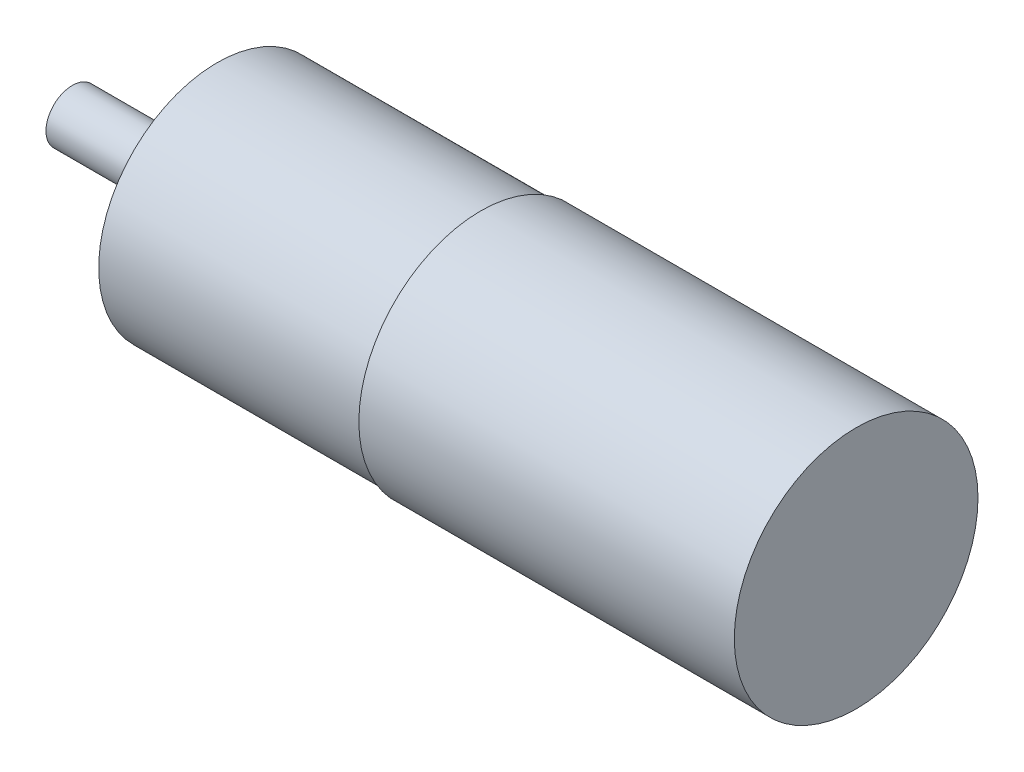
SolidWorks part; units mm, degrees
material "纯金"
ref_plane "前视基准面" through (0, 0, 0) normal (0, 0, 1) x (1, 0, 0)
ref_plane "上视基准面" through (0, 0, 0) normal (0, 1, 0) x (1, 0, 0)
ref_plane "右视基准面" through (0, 0, 0) normal (1, 0, 0) x (0, 0, -1)
sketch "草图1" plane through (0, 0, 0) normal (1, 0, 0) x (0, 0, -1)
  circle A0 centre (0, 0) radius 18
  dimension "D1" = 36
extrude "凸台-拉伸1" add sketch "草图1" along normal blind 40
sketch "草图2" plane through (0, 0, 0) normal (-1, 0, 0) x (0, 0, 1)
  circle A0 centre (0, 0) radius 11
  dimension "D1" = 22
extrude "凸台-拉伸2" add sketch "草图2" along normal blind 2
sketch "草图3" plane through (-2, 0, 0) normal (-1, 0, 0) x (0, 0, 1)
  circle A0 centre (0, 0) radius 4
  dimension "D1" = 8
extrude "凸台-拉伸3" add sketch "草图3" along normal blind 20
sketch "草图4" plane through (0, 0, 0) normal (-1, 0, 0) x (0, 0, 1)
  circle A0 centre (-14, 0) radius 1.5
  circle A1 centre (0, 0) radius 18 construction
  dimension "D1" = 3
  dimension "D3" = 14
  dimension "D2" = 14
extrude "切除-拉伸1" cut sketch "草图4" against normal blind 5
pattern_circular "阵列(圆周)1" count 4 every 90 about axis through (0, 0, 0) along (1, 0, 0) of "切除-拉伸1"
sketch "草图5" plane through (-22, 0, 0) normal (-1, 0, 0) x (0, 0, 1)
  line L0 (-3.7731, -1.3281) -> (1.382, -3.7537)
  arc A0 (-3.7731, -1.3281) -> (1.382, -3.7537) centre (0, 0) ccw
  circle A1 centre (0, 0) radius 4 construction
  point P6 (-1.6968, 3.6223)
  point P7 (1.382, -3.7537)
extrude "切除-拉伸2" cut sketch "草图5" against normal blind 15
sketch "草图6" plane through (40, 0, 0) normal (1, 0, 0) x (0, 0, -1)
  circle A0 centre (0, 0) radius 18.5
  dimension "D1" = 37
extrude "凸台-拉伸4" add sketch "草图6" along normal blind 57
